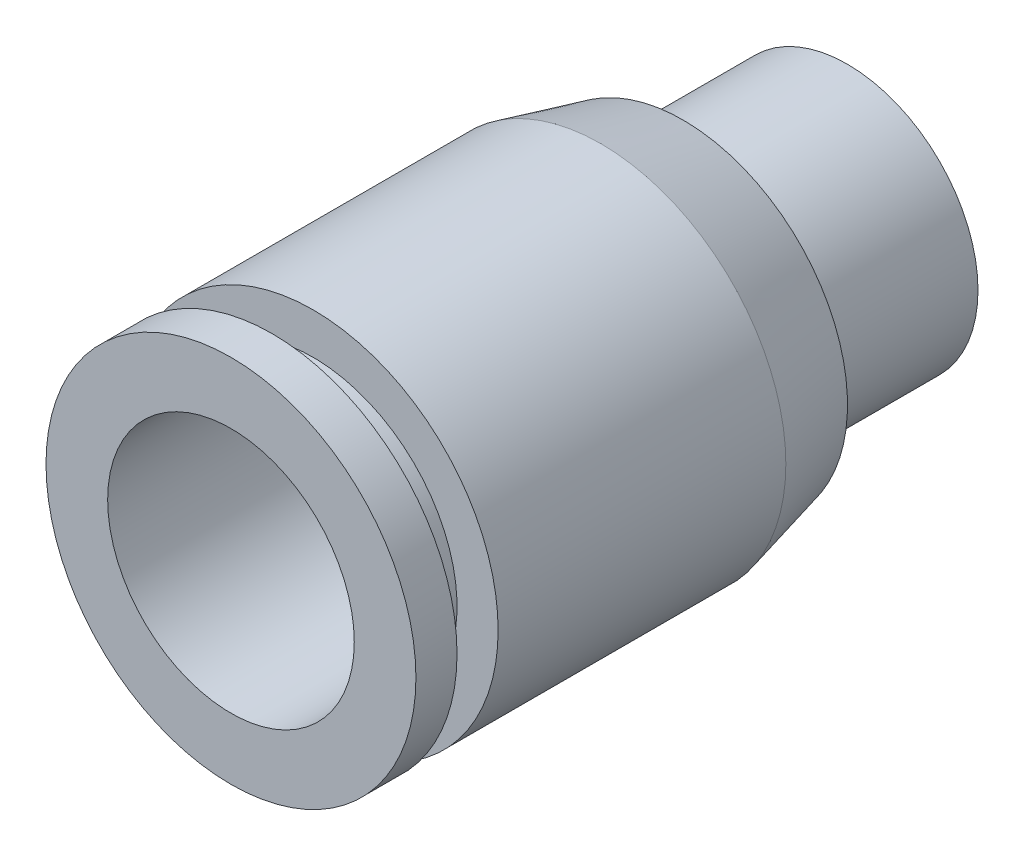
SolidWorks part; units mm, degrees
ref_plane "Front Plane" through (0, 0, 0) normal (0, 0, 1) x (1, 0, 0)
ref_plane "Top Plane" through (0, 0, 0) normal (0, 1, 0) x (1, 0, 0)
ref_plane "Right Plane" through (0, 0, 0) normal (1, 0, 0) x (0, 0, -1)
ref_axis "Axis1" through (0, 0, -4.7) along (0, 0, 1)
sketch "Sketch2" plane through (0, 0, 0) normal (1, 0, 0) x (0, 0, -1)
  line L0 (-2, 3) -> (-11, 3)
  line L1 (-11, 3) -> (-11, 4.5)
  line L2 (-11, 4.5) -> (-10, 4.5)
  line L3 (-10, 4.5) -> (-10, 3.5)
  line L4 (-10, 3.5) -> (-9, 3.5)
  line L5 (-9, 3.5) -> (-9, 4.5)
  line L6 (-9, 4.5) -> (-2, 4.5)
  line L8 (-2, 4.5) -> (0, 4)
  line L9 (0, 3.175) -> (4, 3.175)
  line L10 (-2, 3) -> (-2, 2)
  line L11 (-2, 2) -> (4, 2)
  line L12 (4, 2) -> (4, 3.175)
  line L13 (0, 4) -> (0, 3.175)
revolve "Revolve1" add sketch "Sketch2" angle 360 about axis through (0, 0, -4.7) along (0, 0, 1)
